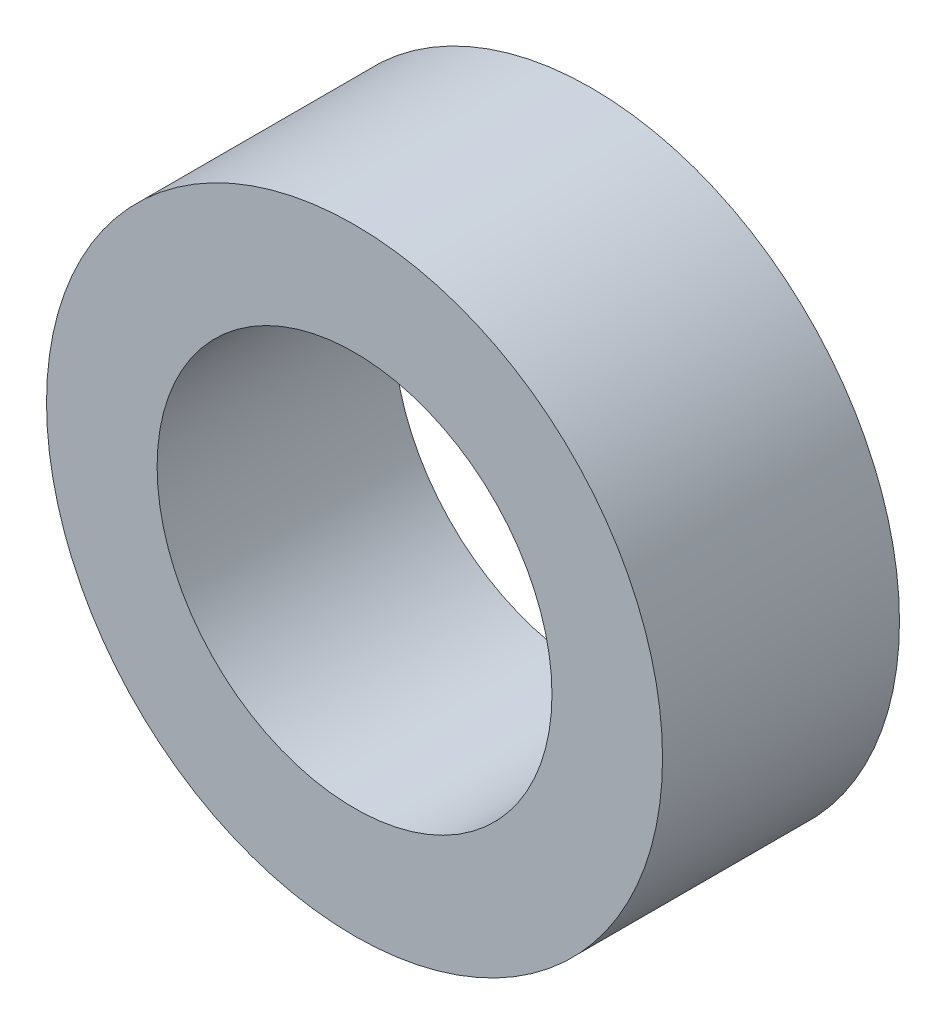
SolidWorks part; units mm, degrees
material "Nylon 101"
ref_plane "Front Plane" through (0, 0, 0) normal (0, 0, 1) x (1, 0, 0)
ref_plane "Top Plane" through (0, 0, 0) normal (0, 1, 0) x (1, 0, 0)
ref_plane "Right Plane" through (0, 0, 0) normal (1, 0, 0) x (0, 0, -1)
sketch "Sketch1" plane through (0, 0, 0) normal (0, 0, 1) x (1, 0, 0)
  circle A0 centre (0, 0) radius 3.9
  circle A1 centre (0, 0) radius 2.5
  dimension "D1" = 7.8
  dimension "D2" = 5
extrude "Extrude1" add sketch "Sketch1" along normal blind 3
